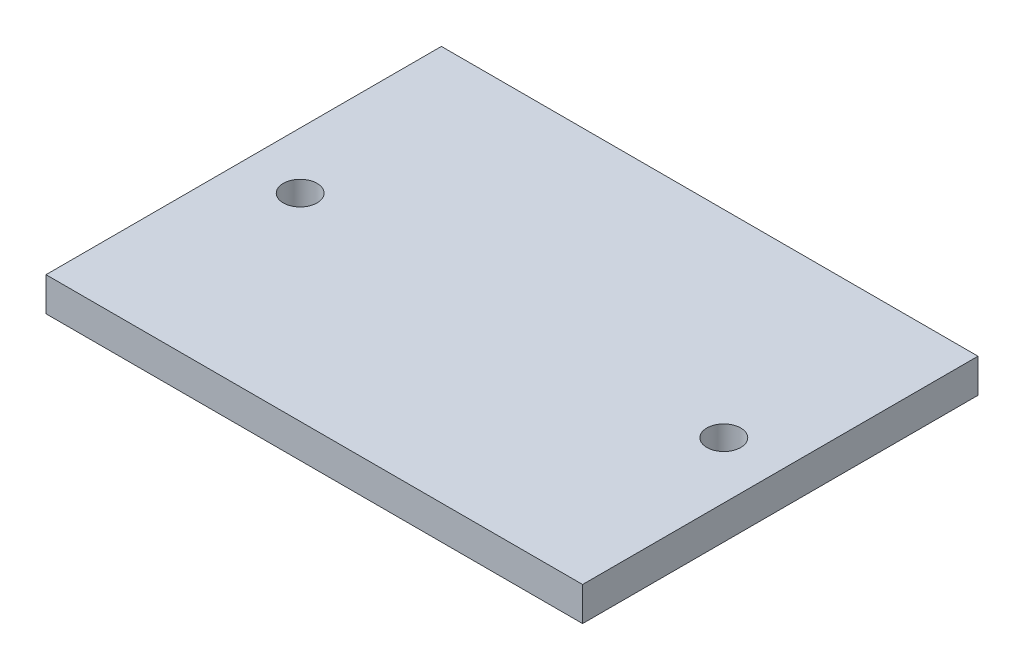
SolidWorks part; units mm, degrees
ref_plane "Front Plane" through (0, 0, 0) normal (0, 0, 1) x (1, 0, 0)
ref_plane "Top Plane" through (0, 0, 0) normal (0, 1, 0) x (1, 0, 0)
ref_plane "Right Plane" through (0, 0, 0) normal (1, 0, 0) x (0, 0, -1)
sketch "Sketch1" plane through (0, 0, 0) normal (0, 1, 0) x (1, 0, 0)
  line L1 (0, 0) -> (47.5, 0)
  line L2 (0, 0) -> (0, 35)
  line L3 (0, 35) -> (47.5, 35)
  line L4 (47.5, 0) -> (47.5, 35)
  dimension "D1" = 35
  dimension "D2" = 47.5
extrude "Boss-Extrude1" add sketch "Sketch1" along normal blind 3
hole_wizard "Ø3.0mm Dowel Hole1" positions "Sketch2" profile "Sketch3" hole size "Ø3.0" standard "ANSI Metric" end condition up to next
sketch "Sketch2" plane through (0, 3, 0) normal (0, 1, 0) x (1, 0, 0)
  line L0 (0, 17.5) -> (47.5, 17.5) construction
  line L1 (0, 35) -> (0, 0) construction
  line L2 (47.5, 0) -> (47.5, 35) construction
  line L4 (0, 0) -> (47.5, 0) construction
  point P0 (5, 17.5)
  point P2 (42.5, 17.5)
  point P15 (0, 0)
  point P16 (0, 0)
  dimension "D1" = 17.5
  dimension "D2" = 5
  dimension "D3" = 5
sketch "Sketch3" plane through (5, 3, -17.5) normal (1, 0, 0) x (0, 0, 1)
  line L0 (0, 0) -> (0, 3)
  line L1 (0, 3) -> (1.5, 3)
  line L2 (1.5, 3) -> (1.5, 0)
  line L5 (1.5, 0) -> (0, 0)
  line L11 (0, -6.35) -> (0, 107.95) construction
  dimension "Thru Hole Dia." = 3
  dimension "Thru Hole Depth" = 3
